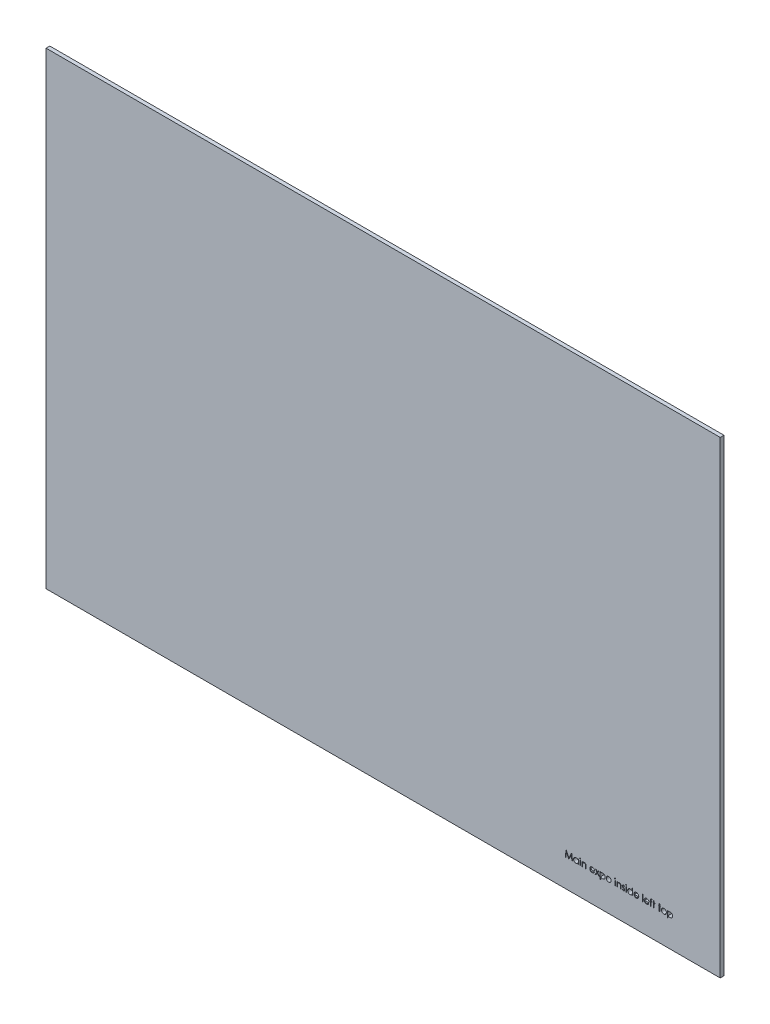
SolidWorks part; units mm, degrees
ref_plane "Front Plane" through (0, 0, 0) normal (0, 0, 1) x (1, 0, 0)
ref_plane "Top Plane" through (0, 0, 0) normal (0, 1, 0) x (1, 0, 0)
ref_plane "Right Plane" through (0, 0, 0) normal (1, 0, 0) x (0, 0, -1)
sketch "Sketch1" plane through (0, 0, 0) normal (0, 0, 1) x (1, 0, 0)
  line L1 (0, 0) -> (360, 0)
  line L2 (0, 0) -> (0, -250)
  line L3 (0, -250) -> (360, -250)
  line L4 (360, 0) -> (360, -250)
  dimension "D1" = 360
  dimension "D2" = 250
extrude "Boss-Extrude1" add sketch "Sketch1" along normal blind 2
sketch "Sketch2" plane through (0, 0, 2) normal (0, 0, 1) x (1, 0, 0)
  line L0 (276.9828, -235.434) -> (341.8174, -235.434) construction
  line L1 (277.2521, -235.434) -> (277.7141, -231.934)
  line L2 (277.7141, -231.934) -> (277.759, -231.934)
  line L3 (277.759, -231.934) -> (279.204, -234.8058)
  line L4 (279.204, -234.8058) -> (280.6455, -231.934)
  line L5 (280.6455, -231.934) -> (280.6911, -231.934)
  line L6 (280.6911, -231.934) -> (281.1559, -235.434)
  line L7 (281.1559, -235.434) -> (280.8404, -235.434)
  line L8 (280.8404, -235.434) -> (280.5053, -232.9156)
  line L9 (280.5053, -232.9156) -> (279.2419, -235.434)
  line L10 (279.2419, -235.434) -> (279.171, -235.434)
  line L11 (279.171, -235.434) -> (277.9027, -232.91)
  line L12 (277.9027, -232.91) -> (277.5683, -235.434)
  line L13 (277.5683, -235.434) -> (277.2521, -235.434)
  line L14 (284.3867, -232.8763) -> (284.3867, -235.434)
  line L15 (284.3867, -235.434) -> (284.0726, -235.434)
  line L16 (284.0726, -235.434) -> (284.0726, -234.9916)
  line L17 (284.0726, -233.3496) -> (284.0726, -232.8763)
  line L18 (284.0726, -232.8763) -> (284.3867, -232.8763)
  line L19 (285.0598, -232.8763) -> (285.3739, -232.8763)
  line L20 (285.3739, -232.8763) -> (285.3739, -235.434)
  line L21 (285.3739, -235.434) -> (285.0598, -235.434)
  line L22 (285.0598, -235.434) -> (285.0598, -232.8763)
  line L23 (286.1367, -232.8763) -> (286.4508, -232.8763)
  line L24 (286.4508, -232.8763) -> (286.4508, -233.3376)
  line L25 (288.3803, -234.1278) -> (288.3803, -235.434)
  line L26 (288.3803, -235.434) -> (288.0662, -235.434)
  line L27 (288.0662, -235.434) -> (288.0662, -234.2309)
  line L28 (286.4508, -234.5092) -> (286.4508, -235.434)
  line L29 (286.4508, -235.434) -> (286.1367, -235.434)
  line L30 (286.1367, -235.434) -> (286.1367, -232.8763)
  line L31 (292.5435, -234.6263) -> (292.8226, -234.7728)
  line L32 (292.9572, -234.2225) -> (290.6687, -234.2225)
  line L33 (290.7017, -233.9084) -> (292.6431, -233.9084)
  line L34 (293.361, -232.8763) -> (293.7347, -232.8763)
  line L35 (293.7347, -232.8763) -> (294.3931, -233.799)
  line L36 (294.3931, -233.799) -> (295.0515, -232.8763)
  line L37 (295.0515, -232.8763) -> (295.4251, -232.8763)
  line L38 (295.4251, -232.8763) -> (294.5803, -234.0605)
  line L39 (294.5803, -234.0605) -> (295.5598, -235.434)
  line L40 (295.5598, -235.434) -> (295.1861, -235.434)
  line L41 (295.1861, -235.434) -> (294.3931, -234.3227)
  line L42 (294.3931, -234.3227) -> (293.6001, -235.434)
  line L43 (293.6001, -235.434) -> (293.2264, -235.434)
  line L44 (293.2264, -235.434) -> (294.2066, -234.0605)
  line L45 (294.2066, -234.0605) -> (293.361, -232.8763)
  line L46 (295.9187, -232.8763) -> (296.2328, -232.8763)
  line L47 (296.2328, -232.8763) -> (296.2328, -233.3496)
  line L48 (296.2328, -234.9706) -> (296.2328, -236.3763)
  line L49 (296.2328, -236.3763) -> (295.9187, -236.3763)
  line L50 (295.9187, -236.3763) -> (295.9187, -232.8763)
  line L51 (303.7264, -232.8763) -> (304.0405, -232.8763)
  line L52 (304.0405, -232.8763) -> (304.0405, -235.434)
  line L53 (304.0405, -235.434) -> (303.7264, -235.434)
  line L54 (303.7264, -235.434) -> (303.7264, -232.8763)
  line L55 (304.8034, -232.8763) -> (305.1175, -232.8763)
  line L56 (305.1175, -232.8763) -> (305.1175, -233.3376)
  line L57 (307.0469, -234.1278) -> (307.0469, -235.434)
  line L58 (307.0469, -235.434) -> (306.7328, -235.434)
  line L59 (306.7328, -235.434) -> (306.7328, -234.2309)
  line L60 (305.1175, -234.5092) -> (305.1175, -235.434)
  line L61 (305.1175, -235.434) -> (304.8034, -235.434)
  line L62 (304.8034, -235.434) -> (304.8034, -232.8763)
  line L63 (308.9764, -233.1953) -> (308.7633, -233.4148)
  line L64 (307.5405, -235.1325) -> (307.7488, -234.8955)
  line L65 (309.6046, -232.8763) -> (309.9187, -232.8763)
  line L66 (309.9187, -232.8763) -> (309.9187, -235.434)
  line L67 (309.9187, -235.434) -> (309.6046, -235.434)
  line L68 (309.6046, -235.434) -> (309.6046, -232.8763)
  line L69 (313.2841, -231.8443) -> (313.2841, -235.434)
  line L70 (313.2841, -235.434) -> (312.97, -235.434)
  line L71 (312.97, -235.434) -> (312.97, -234.9916)
  line L72 (312.97, -233.3713) -> (312.97, -231.8443)
  line L73 (312.97, -231.8443) -> (313.2841, -231.8443)
  line L74 (316.1012, -234.6263) -> (316.3803, -234.7728)
  line L75 (316.5149, -234.2225) -> (314.2264, -234.2225)
  line L76 (314.2594, -233.9084) -> (316.2008, -233.9084)
  line L77 (318.4444, -231.8443) -> (318.7585, -231.8443)
  line L78 (318.7585, -231.8443) -> (318.7585, -235.434)
  line L79 (318.7585, -235.434) -> (318.4444, -235.434)
  line L80 (318.4444, -235.434) -> (318.4444, -231.8443)
  line L81 (321.5756, -234.6263) -> (321.8546, -234.7728)
  line L82 (321.9893, -234.2225) -> (319.7008, -234.2225)
  line L83 (319.7337, -233.9084) -> (321.6751, -233.9084)
  line L84 (323.6944, -231.8653) -> (323.6944, -232.192)
  line L85 (323.1132, -232.5215) -> (323.1132, -232.8763)
  line L86 (323.1132, -232.8763) -> (323.6495, -232.8763)
  line L87 (323.6495, -232.8763) -> (323.6495, -233.1904)
  line L88 (323.6495, -233.1904) -> (323.1124, -233.1904)
  line L89 (323.1124, -233.1904) -> (323.111, -235.434)
  line L90 (323.111, -235.434) -> (322.7969, -235.434)
  line L91 (322.7969, -235.434) -> (322.7969, -233.1904)
  line L92 (322.7969, -233.1904) -> (322.438, -233.1904)
  line L93 (322.438, -233.1904) -> (322.438, -232.8763)
  line L94 (322.438, -232.8763) -> (322.7969, -232.8763)
  line L95 (322.7969, -232.8763) -> (322.7969, -232.4676)
  line L96 (324.4572, -231.8443) -> (324.7713, -231.8443)
  line L97 (324.7713, -231.8443) -> (324.7713, -232.8763)
  line L98 (324.7713, -232.8763) -> (325.22, -232.8763)
  line L99 (325.22, -232.8763) -> (325.22, -233.1904)
  line L100 (325.22, -233.1904) -> (324.7713, -233.1904)
  line L101 (324.7713, -233.1904) -> (324.7713, -235.434)
  line L102 (324.7713, -235.434) -> (324.4572, -235.434)
  line L103 (324.4572, -235.434) -> (324.4572, -233.1904)
  line L104 (324.4572, -233.1904) -> (324.0085, -233.1904)
  line L105 (324.0085, -233.1904) -> (324.0085, -232.8763)
  line L106 (324.0085, -232.8763) -> (324.4572, -232.8763)
  line L107 (324.4572, -232.8763) -> (324.4572, -231.8443)
  line L108 (327.4187, -231.8443) -> (327.7328, -231.8443)
  line L109 (327.7328, -231.8443) -> (327.7328, -232.8763)
  line L110 (327.7328, -232.8763) -> (328.1816, -232.8763)
  line L111 (328.1816, -232.8763) -> (328.1816, -233.1904)
  line L112 (328.1816, -233.1904) -> (327.7328, -233.1904)
  line L113 (327.7328, -233.1904) -> (327.7328, -235.434)
  line L114 (327.7328, -235.434) -> (327.4187, -235.434)
  line L115 (327.4187, -235.434) -> (327.4187, -233.1904)
  line L116 (327.4187, -233.1904) -> (326.97, -233.1904)
  line L117 (326.97, -233.1904) -> (326.97, -232.8763)
  line L118 (326.97, -232.8763) -> (327.4187, -232.8763)
  line L119 (327.4187, -232.8763) -> (327.4187, -231.8443)
  line L120 (331.9059, -232.8763) -> (332.22, -232.8763)
  line L121 (332.22, -232.8763) -> (332.22, -233.3496)
  line L122 (332.22, -234.9706) -> (332.22, -236.3763)
  line L123 (332.22, -236.3763) -> (331.9059, -236.3763)
  line L124 (331.9059, -236.3763) -> (331.9059, -232.8763)
  spline S0 degree 3 poles (284.0726, -234.9916) (284.0053, -235.071) (283.8968, -235.1816) (283.7302, -235.2962) (283.6015, -235.3644) (283.4666, -235.4155) (283.2766, -235.4649) (283.1281, -235.4797) (283.0279, -235.4789) knots 0 0 0 0 0.262085 0.38627 0.507165 0.6273 0.748145 1 1 1 1
  spline S1 degree 3 poles (283.0279, -235.4789) (282.9389, -235.4787) (282.8066, -235.4672) (282.6366, -235.4263) (282.5153, -235.3844) (282.3996, -235.3288) (282.2885, -235.2623) (282.1827, -235.1831) (282.0836, -235.0925) (281.9924, -234.9941) (281.9123, -234.8891) (281.8456, -234.7781) (281.7897, -234.6624) (281.7468, -234.5411) (281.7061, -234.3703) (281.6946, -234.2376) (281.6944, -234.1481) knots 0 0 0 0 0.127433 0.189004 0.24993 0.310668 0.372329 0.434939 0.499576 0.564191 0.626735 0.688109 0.749294 0.810331 0.871901 1 1 1 1
  spline S2 degree 3 poles (281.6944, -234.1481) (281.6949, -234.0603) (281.7056, -233.9297) (281.7476, -233.762) (281.7911, -233.6426) (281.847, -233.5283) (281.9149, -233.4189) (281.9949, -233.3141) (282.0872, -233.2164) (282.1871, -233.1262) (282.294, -233.0478) (282.4053, -232.9801) (282.5225, -232.9264) (282.6441, -232.8831) (282.8153, -232.8424) (282.9483, -232.8322) (283.0377, -232.8314) knots 0 0 0 0 0.126079 0.186904 0.247574 0.308003 0.369132 0.432033 0.496791 0.561611 0.624914 0.686726 0.748079 0.809582 0.871631 1 1 1 1
  spline S3 degree 3 poles (283.0377, -232.8314) (283.1399, -232.8317) (283.2917, -232.8449) (283.4837, -232.8988) (283.6183, -232.9527) (283.7455, -233.0244) (283.9074, -233.1475) (284.0107, -233.2646) (284.0726, -233.3496) knots 0 0 0 0 0.254654 0.376015 0.495255 0.614798 0.738106 1 1 1 1
  spline S4 degree 3 poles (283.0419, -233.1455) (282.9514, -233.1459) (282.8161, -233.1609) (282.645, -233.2175) (282.5241, -233.2747) (282.4114, -233.3468) (282.3107, -233.4339) (282.2212, -233.5337) (282.1459, -233.6458) (282.0846, -233.766) (282.0267, -233.9331) (282.0073, -234.0642) (282.0085, -234.1516) knots 0 0 0 0 0.169593 0.252476 0.336244 0.419505 0.502036 0.584775 0.669846 0.754185 0.836658 1 1 1 1
  spline S5 degree 3 poles (282.0085, -234.1516) (282.0092, -234.2386) (282.0259, -234.3701) (282.0858, -234.5369) (282.1469, -234.6581) (282.2236, -234.7707) (282.3125, -234.8725) (282.4145, -234.96) (282.5274, -235.0332) (282.648, -235.0923) (282.8175, -235.1477) (282.9502, -235.1652) (283.0391, -235.1648) knots 0 0 0 0 0.162859 0.245484 0.330807 0.416493 0.499893 0.583048 0.667158 0.751312 0.833785 1 1 1 1
  spline S6 degree 3 poles (283.0391, -235.1648) (283.1294, -235.1644) (283.2651, -235.1488) (283.4379, -235.0927) (283.5617, -235.0349) (283.677, -234.9631) (283.7805, -234.8791) (283.868, -234.7814) (283.9422, -234.674) (284.0003, -234.5563) (284.0579, -234.3869) (284.0721, -234.2514) (284.0726, -234.1608) knots 0 0 0 0 0.168664 0.252552 0.33824 0.423103 0.505556 0.586176 0.667136 0.748499 0.830452 1 1 1 1
  spline S7 degree 3 poles (284.0726, -234.1608) (284.0724, -234.0912) (284.0635, -233.9882) (284.0323, -233.856) (284, -233.7626) (283.9575, -233.6739) (283.9063, -233.5895) (283.8454, -233.5096) (283.7758, -233.4355) (283.6996, -233.3678) (283.619, -233.3075) (283.533, -233.2579) (283.4431, -233.2168) (283.3491, -233.1842) (283.2155, -233.1545) (283.112, -233.1445) (283.0419, -233.1455) knots 0 0 0 0 0.129188 0.191219 0.251913 0.312507 0.373494 0.435152 0.498741 0.562095 0.624187 0.685476 0.746097 0.807612 0.869967 1 1 1 1
  spline S8 degree 3 poles (285.2154, -231.7994) (285.2534, -231.7995) (285.3108, -231.8082) (285.3785, -231.8429) (285.4231, -231.8774) (285.4613, -231.918) (285.4973, -231.9811) (285.5087, -232.0344) (285.5085, -232.07) knots 0 0 0 0 0.258284 0.384341 0.51198 0.638632 0.75923 1 1 1 1
  spline S9 degree 3 poles (285.5085, -232.07) (285.5086, -232.105) (285.4972, -232.1574) (285.4611, -232.2194) (285.4231, -232.2599) (285.3785, -232.2943) (285.3108, -232.3291) (285.2534, -232.3378) (285.2154, -232.3378) knots 0 0 0 0 0.237546 0.357497 0.484917 0.613329 0.74015 1 1 1 1
  spline S10 degree 3 poles (285.2154, -232.3378) (285.178, -232.3381) (285.1215, -232.3287) (285.0544, -232.2943) (285.0098, -232.2601) (284.9726, -232.2191) (284.9363, -232.1575) (284.9251, -232.1049) (284.9251, -232.07) knots 0 0 0 0 0.256661 0.384213 0.513365 0.640443 0.761085 1 1 1 1
  spline S11 degree 3 poles (284.9251, -232.07) (284.925, -232.0344) (284.9362, -231.981) (284.9724, -231.9182) (285.0098, -231.8772) (285.0544, -231.843) (285.1215, -231.8086) (285.178, -231.7991) (285.2154, -231.7994) knots 0 0 0 0 0.242149 0.363437 0.489745 0.618115 0.744894 1 1 1 1
  spline S12 degree 3 poles (286.4508, -233.3376) (286.5141, -233.2554) (286.615, -233.1405) (286.7724, -233.02) (286.8923, -232.9498) (287.018, -232.897) (287.1935, -232.8454) (287.3315, -232.8319) (287.4239, -232.8314) knots 0 0 0 0 0.273569 0.398988 0.51993 0.63811 0.756589 1 1 1 1
  spline S13 degree 3 poles (287.4239, -232.8314) (287.5163, -232.832) (287.6542, -232.847) (287.8248, -232.9098) (287.9414, -232.973) (288.0465, -233.0516) (288.1388, -233.1432) (288.2152, -233.2485) (288.2664, -233.3462) (288.3001, -233.4329) (288.3214, -233.5071) (288.3394, -233.5899) (288.355, -233.6808) (288.3656, -233.7806) (288.3772, -233.9303) (288.3811, -234.0471) (288.3803, -234.1278) knots 0 0 0 0 0.151178 0.223488 0.295543 0.366976 0.437131 0.507044 0.57856 0.616614 0.658756 0.704491 0.754803 0.809332 0.868274 1 1 1 1
  spline S14 degree 3 poles (288.0662, -234.2309) (288.0657, -234.1643) (288.0656, -234.0689) (288.0616, -233.9476) (288.0577, -233.8702) (288.0519, -233.802) (288.0445, -233.729) (288.0361, -233.679) (288.029, -233.6489) knots 0 0 0 0 0.34211 0.489826 0.623254 0.74008 0.841483 1 1 1 1
  spline S15 degree 3 poles (288.029, -233.6489) (288.0115, -233.5721) (287.9718, -233.4625) (287.8836, -233.3409) (287.8057, -233.2687) (287.7145, -233.2126) (287.57, -233.1584) (287.4509, -233.1451) (287.3693, -233.1455) knots 0 0 0 0 0.260833 0.378476 0.493178 0.609281 0.729981 1 1 1 1
  spline S16 degree 3 poles (287.3693, -233.1455) (287.3193, -233.1453) (287.2446, -233.151) (287.1479, -233.1719) (287.0775, -233.1927) (287.01, -233.2214) (286.9432, -233.2539) (286.8797, -233.2945) (286.8181, -233.3397) (286.7608, -233.3897) (286.7075, -233.4426) (286.6599, -233.4989) (286.6169, -233.5577) (286.5797, -233.6198) (286.5362, -233.7065) (286.5118, -233.7756) (286.4992, -233.8228) knots 0 0 0 0 0.126627 0.188984 0.25023 0.312351 0.374574 0.438148 0.50292 0.567974 0.630771 0.692935 0.754398 0.815218 0.876117 1 1 1 1
  spline S17 degree 3 poles (286.4992, -233.8228) (286.4898, -233.8602) (286.4794, -233.9217) (286.469, -234.0106) (286.4619, -234.0915) (286.4576, -234.1822) (286.4511, -234.3224) (286.4513, -234.4326) (286.4508, -234.5092) knots 0 0 0 0 0.167615 0.271052 0.38946 0.520843 0.666399 1 1 1 1
  spline S18 degree 3 poles (292.8226, -234.7728) (292.7811, -234.8505) (292.7116, -234.9595) (292.6047, -235.0893) (292.5196, -235.171) (292.4299, -235.2423) (292.3352, -235.3046) (292.2349, -235.3577) (292.129, -235.4025) (292.0167, -235.4369) (291.8544, -235.4702) (291.7275, -235.4789) (291.6412, -235.4789) knots 0 0 0 0 0.181661 0.265874 0.346355 0.4246 0.501903 0.579992 0.658443 0.738672 0.821894 1 1 1 1
  spline S19 degree 3 poles (291.6412, -235.4789) (291.5454, -235.4788) (291.4045, -235.4678) (291.2253, -235.4247) (291.1021, -235.3808) (290.9873, -235.3233) (290.8808, -235.2534) (290.782, -235.1712) (290.694, -235.0762) (290.6147, -234.9745) (290.5448, -234.8686) (290.4863, -234.7586) (290.4388, -234.6453) (290.4004, -234.5295) (290.3643, -234.369) (290.3556, -234.2452) (290.3546, -234.1622) knots 0 0 0 0 0.139629 0.204797 0.268135 0.329814 0.391301 0.453434 0.516552 0.579631 0.641119 0.701294 0.76081 0.819932 0.87892 1 1 1 1
  spline S20 degree 3 poles (290.3546, -234.1622) (290.3556, -234.0844) (290.3629, -233.9682) (290.3945, -233.8177) (290.4266, -233.7088) (290.4682, -233.6033) (290.5364, -233.4658) (290.6016, -233.3697) (290.6491, -233.3082) knots 0 0 0 0 0.253768 0.377428 0.500551 0.623296 0.746578 1 1 1 1
  spline S21 degree 3 poles (290.6491, -233.3082) (290.7097, -233.2325) (290.8084, -233.1266) (290.9631, -233.0158) (291.0847, -232.9478) (291.215, -232.8962) (291.4016, -232.8437) (291.5495, -232.8326) (291.6489, -232.8314) knots 0 0 0 0 0.253589 0.374643 0.49534 0.616325 0.739759 1 1 1 1
  spline S22 degree 3 poles (291.6489, -232.8314) (291.7517, -232.831) (291.9036, -232.8459) (292.0962, -232.8992) (292.2301, -232.9543) (292.3557, -233.0255) (292.514, -233.1445) (292.6175, -233.2542) (292.6789, -233.3348) knots 0 0 0 0 0.259033 0.38188 0.502258 0.622752 0.744743 1 1 1 1
  spline S23 degree 3 poles (292.6789, -233.3348) (292.7247, -233.3937) (292.7847, -233.4894) (292.8483, -233.6262) (292.8866, -233.735) (292.9176, -233.8489) (292.9483, -234.0112) (292.9556, -234.1372) (292.9572, -234.2225) knots 0 0 0 0 0.236255 0.356174 0.47725 0.60154 0.729618 1 1 1 1
  spline S24 degree 3 poles (290.6687, -234.2225) (290.6705, -234.2887) (290.6794, -234.3866) (290.7097, -234.5118) (290.7409, -234.5989) (290.7788, -234.6818) (290.8252, -234.76) (290.8805, -234.833) (290.9423, -234.9016) (291.011, -234.9626) (291.0832, -235.0173) (291.1601, -235.0631) (291.241, -235.1003) (291.3258, -235.1293) (291.4458, -235.1564) (291.5389, -235.1651) (291.6019, -235.1648) knots 0 0 0 0 0.134476 0.198391 0.260753 0.321829 0.383037 0.444653 0.507398 0.569825 0.630778 0.690929 0.750945 0.811049 0.872331 1 1 1 1
  spline S25 degree 3 poles (291.6019, -235.1648) (291.6641, -235.1651) (291.7574, -235.1577) (291.8793, -235.1322) (291.9685, -235.1064) (292.0541, -235.0748) (292.1333, -235.0367) (292.2062, -234.9945) (292.2743, -234.9463) (292.3404, -234.8873) (292.4339, -234.7825) (292.501, -234.6929) (292.5435, -234.6263) knots 0 0 0 0 0.163879 0.245659 0.327726 0.40861 0.485749 0.559169 0.630268 0.705306 0.792065 1 1 1 1
  spline S26 degree 3 poles (292.6431, -233.9084) (292.6232, -233.8276) (292.5836, -233.7137) (292.5111, -233.5768) (292.4496, -233.4912) (292.3797, -233.4152) (292.2991, -233.3488) (292.2086, -233.2894) (292.1089, -233.2392) (292.0032, -233.1966) (291.8554, -233.158) (291.7415, -233.1444) (291.665, -233.1455) knots 0 0 0 0 0.185231 0.267501 0.3444 0.419595 0.496891 0.576638 0.660268 0.745387 0.83004 1 1 1 1
  spline S27 degree 3 poles (291.665, -233.1455) (291.6031, -233.1454) (291.5111, -233.1521) (291.3927, -233.1778) (291.308, -233.2037) (291.2274, -233.2384) (291.1224, -233.2928) (291.0515, -233.347) (291.006, -233.3853) knots 0 0 0 0 0.259141 0.384162 0.505992 0.629098 0.750669 1 1 1 1
  spline S28 degree 3 poles (291.006, -233.3853) (290.9711, -233.4147) (290.9239, -233.4656) (290.8672, -233.5404) (290.8278, -233.6034) (290.7917, -233.672) (290.7455, -233.7726) (290.7181, -233.853) (290.7017, -233.9084) knots 0 0 0 0 0.22258 0.3385 0.458709 0.585535 0.717518 1 1 1 1
  spline S29 degree 3 poles (296.2328, -233.3496) (296.295, -233.2643) (296.3994, -233.1483) (296.5607, -233.0241) (296.6878, -232.9527) (296.8223, -232.899) (297.0135, -232.8448) (297.1646, -232.8318) (297.2663, -232.8314) knots 0 0 0 0 0.263045 0.386061 0.505771 0.625178 0.746148 1 1 1 1
  spline S30 degree 3 poles (297.2663, -232.8314) (297.3559, -232.8323) (297.4892, -232.8423) (297.6606, -232.8831) (297.7822, -232.9264) (297.8995, -232.9801) (298.0107, -233.0478) (298.1176, -233.1262) (298.2175, -233.2164) (298.3098, -233.3141) (298.3897, -233.4191) (298.4586, -233.5281) (298.5142, -233.6427) (298.5578, -233.762) (298.5998, -233.9297) (298.6105, -234.0603) (298.611, -234.1481) knots 0 0 0 0 0.128636 0.190653 0.252125 0.313446 0.375227 0.438498 0.503285 0.56801 0.630879 0.692154 0.752552 0.813191 0.873985 1 1 1 1
  spline S31 degree 3 poles (298.611, -234.1481) (298.6108, -234.2377) (298.5993, -234.3703) (298.5587, -234.5411) (298.5157, -234.6623) (298.46, -234.7783) (298.3923, -234.8889) (298.3124, -234.9941) (298.2211, -235.0925) (298.1221, -235.1831) (298.0162, -235.2623) (297.9051, -235.3288) (297.7894, -235.3844) (297.6682, -235.4263) (297.4979, -235.4672) (297.3654, -235.4785) (297.2761, -235.4789) knots 0 0 0 0 0.128034 0.189574 0.25058 0.311733 0.37325 0.435763 0.500346 0.564949 0.627528 0.689157 0.749865 0.81076 0.8723 1 1 1 1
  spline S32 degree 3 poles (297.2761, -235.4789) (297.1756, -235.48) (297.0271, -235.4629) (296.8368, -235.4103) (296.7026, -235.3537) (296.5745, -235.2814) (296.4094, -235.1619) (296.3004, -235.0507) (296.2328, -234.9706) knots 0 0 0 0 0.250548 0.37123 0.492116 0.613401 0.737997 1 1 1 1
  spline S33 degree 3 poles (297.2635, -233.1455) (297.1934, -233.1445) (297.09, -233.1546) (296.9563, -233.1842) (296.8622, -233.2171) (296.7719, -233.2575) (296.6862, -233.3079) (296.6052, -233.3676) (296.529, -233.4353) (296.4601, -233.5098) (296.3991, -233.5894) (296.3479, -233.6739) (296.3054, -233.7626) (296.2731, -233.856) (296.2419, -233.9882) (296.233, -234.0912) (296.2328, -234.1608) knots 0 0 0 0 0.130024 0.192374 0.253884 0.314896 0.375806 0.438242 0.501591 0.564881 0.626533 0.687516 0.748106 0.808796 0.870822 1 1 1 1
  spline S34 degree 3 poles (296.2328, -234.1608) (296.233, -234.2515) (296.2481, -234.3866) (296.3042, -234.5565) (296.3626, -234.6739) (296.4366, -234.7819) (296.5257, -234.8786) (296.6291, -234.9634) (296.7452, -235.0348) (296.8696, -235.0927) (297.0428, -235.1485) (297.1783, -235.1646) (297.2684, -235.1648) knots 0 0 0 0 0.169344 0.251061 0.332326 0.413189 0.494299 0.576654 0.661785 0.747765 0.831967 1 1 1 1
  spline S35 degree 3 poles (297.2684, -235.1648) (297.3569, -235.1653) (297.4891, -235.1474) (297.658, -235.0925) (297.7782, -235.033) (297.891, -234.96) (297.9929, -234.8724) (298.0819, -234.7709) (298.1577, -234.6579) (298.2188, -234.5368) (298.2801, -234.3703) (298.2959, -234.2385) (298.2969, -234.1516) knots 0 0 0 0 0.165574 0.248159 0.332033 0.416257 0.499525 0.583039 0.668596 0.754035 0.83692 1 1 1 1
  spline S36 degree 3 poles (298.2969, -234.1516) (298.2982, -234.0641) (298.2786, -233.9332) (298.2211, -233.7658) (298.1586, -233.6463) (298.0844, -233.5335) (297.9946, -233.4339) (297.894, -233.3468) (297.7813, -233.2747) (297.6604, -233.2175) (297.4894, -233.1609) (297.354, -233.1459) (297.2635, -233.1455) knots 0 0 0 0 0.163349 0.245826 0.330367 0.415198 0.497941 0.580476 0.66374 0.747513 0.830399 1 1 1 1
  spline S37 degree 3 poles (300.4746, -232.8314) (300.5687, -232.8305) (300.7079, -232.844) (300.8861, -232.8887) (301.0119, -232.9339) (301.1302, -232.9946) (301.2826, -233.0921) (301.3842, -233.1849) (301.4464, -233.2528) knots 0 0 0 0 0.258332 0.382134 0.503804 0.624693 0.746871 1 1 1 1
  spline S38 degree 3 poles (301.4464, -233.2528) (301.5034, -233.3151) (301.5798, -233.4151) (301.662, -233.5594) (301.7112, -233.6717) (301.7498, -233.788) (301.787, -233.951) (301.7965, -234.0772) (301.7969, -234.1622) knots 0 0 0 0 0.253834 0.376506 0.498534 0.621368 0.744565 1 1 1 1
  spline S39 degree 3 poles (301.7969, -234.1622) (301.7975, -234.2477) (301.7857, -234.3749) (301.7471, -234.5392) (301.7063, -234.6571) (301.654, -234.771) (301.5901, -234.8804) (301.5142, -234.9855) (301.4282, -235.0855) (301.3331, -235.1777) (301.23, -235.258) (301.1209, -235.3269) (301.0042, -235.3823) (300.8812, -235.426) (300.7051, -235.4678) (300.5676, -235.4785) (300.4746, -235.4789) knots 0 0 0 0 0.123337 0.183265 0.243172 0.302898 0.363774 0.425605 0.489659 0.553785 0.616222 0.677854 0.739517 0.802097 0.865866 1 1 1 1
  spline S40 degree 3 poles (300.4746, -235.4789) (300.3812, -235.4784) (300.2432, -235.468) (300.0667, -235.426) (299.9435, -235.3822) (299.8263, -235.3269) (299.7165, -235.2582) (299.6133, -235.1777) (299.5183, -235.0856) (299.4323, -234.9855) (299.3564, -234.8804) (299.2925, -234.771) (299.2401, -234.6571) (299.1993, -234.5392) (299.1607, -234.3749) (299.149, -234.2477) (299.1495, -234.1622) knots 0 0 0 0 0.134635 0.198324 0.260825 0.322714 0.384555 0.446913 0.510958 0.574931 0.636685 0.697483 0.757134 0.816966 0.876818 1 1 1 1
  spline S41 degree 3 poles (299.1495, -234.1622) (299.15, -234.0775) (299.1596, -233.9515) (299.1966, -233.789) (299.2353, -233.673) (299.2848, -233.5613) (299.366, -233.4165) (299.4437, -233.3174) (299.5001, -233.2549) knots 0 0 0 0 0.255238 0.378679 0.501088 0.622714 0.746241 1 1 1 1
  spline S42 degree 3 poles (299.5001, -233.2549) (299.5617, -233.1861) (299.6642, -233.0942) (299.8162, -232.9947) (299.9359, -232.9352) (300.0616, -232.8884) (300.2404, -232.8441) (300.3801, -232.8306) (300.4746, -232.8314) knots 0 0 0 0 0.252713 0.374819 0.496436 0.617911 0.741288 1 1 1 1
  spline S43 degree 3 poles (300.4732, -233.1455) (300.4062, -233.1457) (300.3067, -233.1548) (300.1787, -233.1859) (300.0873, -233.2184) (299.9997, -233.2605) (299.9157, -233.3122) (299.8353, -233.3729) (299.7599, -233.4423) (299.6907, -233.5182) (299.6303, -233.5991) (299.5788, -233.6836) (299.536, -233.7718) (299.5041, -233.8647) (299.4727, -233.9949) (299.4638, -234.0961) (299.4636, -234.1643) knots 0 0 0 0 0.126044 0.187165 0.247399 0.30838 0.36978 0.432584 0.497641 0.562401 0.625557 0.687332 0.748313 0.809791 0.871768 1 1 1 1
  spline S44 degree 3 poles (299.4636, -234.1643) (299.4638, -234.253) (299.4794, -234.3863) (299.5378, -234.5542) (299.5963, -234.6739) (299.6697, -234.7845) (299.7562, -234.8832) (299.8548, -234.9684) (299.9645, -235.0391) (300.0828, -235.0952) (300.2512, -235.149) (300.3839, -235.1658) (300.4732, -235.1648) knots 0 0 0 0 0.168179 0.251488 0.335841 0.419834 0.502345 0.583649 0.665931 0.748717 0.831047 1 1 1 1
  spline S45 degree 3 poles (300.4732, -235.1648) (300.5625, -235.1657) (300.6951, -235.1493) (300.8631, -235.095) (300.9813, -235.0391) (301.0909, -234.9681) (301.1902, -234.8837) (301.276, -234.7843) (301.3493, -234.6737) (301.4088, -234.5544) (301.4669, -234.3862) (301.4827, -234.253) (301.4828, -234.1643) knots 0 0 0 0 0.168983 0.250908 0.333708 0.416005 0.49766 0.579893 0.663902 0.748466 0.831791 1 1 1 1
  spline S46 degree 3 poles (301.4828, -234.1643) (301.4827, -234.0961) (301.4738, -233.9949) (301.4423, -233.8647) (301.4104, -233.7719) (301.3677, -233.6833) (301.3153, -233.5993) (301.2551, -233.5179) (301.1851, -233.4426) (301.1098, -233.3729) (301.0293, -233.3122) (300.9455, -233.2608) (300.8581, -233.2181) (300.7667, -233.1862) (300.6391, -233.1545) (300.5399, -233.1459) (300.4732, -233.1455) knots 0 0 0 0 0.128274 0.19027 0.251768 0.312769 0.374793 0.43797 0.503047 0.568125 0.63095 0.692369 0.752973 0.813641 0.874355 1 1 1 1
  spline S47 degree 3 poles (303.8821, -231.7994) (303.9201, -231.7995) (303.9775, -231.8082) (304.0452, -231.8429) (304.0898, -231.8774) (304.128, -231.918) (304.164, -231.9811) (304.1754, -232.0344) (304.1751, -232.07) knots 0 0 0 0 0.258284 0.384341 0.51198 0.638632 0.75923 1 1 1 1
  spline S48 degree 3 poles (304.1751, -232.07) (304.1752, -232.105) (304.1639, -232.1574) (304.1278, -232.2194) (304.0898, -232.2599) (304.0452, -232.2943) (303.9775, -232.3291) (303.9201, -232.3378) (303.8821, -232.3378) knots 0 0 0 0 0.237546 0.357497 0.484917 0.613329 0.74015 1 1 1 1
  spline S49 degree 3 poles (303.8821, -232.3378) (303.8447, -232.3381) (303.7882, -232.3287) (303.7211, -232.2943) (303.6764, -232.2601) (303.6393, -232.2191) (303.603, -232.1575) (303.5918, -232.1049) (303.5918, -232.07) knots 0 0 0 0 0.256661 0.384213 0.513365 0.640443 0.761085 1 1 1 1
  spline S50 degree 3 poles (303.5918, -232.07) (303.5917, -232.0344) (303.6029, -231.981) (303.639, -231.9182) (303.6765, -231.8772) (303.7211, -231.843) (303.7882, -231.8086) (303.8447, -231.7991) (303.8821, -231.7994) knots 0 0 0 0 0.242149 0.363437 0.489745 0.618115 0.744894 1 1 1 1
  spline S51 degree 3 poles (305.1175, -233.3376) (305.1808, -233.2554) (305.2817, -233.1405) (305.439, -233.02) (305.559, -232.9498) (305.6846, -232.897) (305.8601, -232.8454) (305.9982, -232.8319) (306.0906, -232.8314) knots 0 0 0 0 0.273569 0.398988 0.51993 0.63811 0.756589 1 1 1 1
  spline S52 degree 3 poles (306.0906, -232.8314) (306.183, -232.832) (306.3209, -232.847) (306.4914, -232.9098) (306.6081, -232.973) (306.7132, -233.0516) (306.8055, -233.1432) (306.8819, -233.2485) (306.9331, -233.3462) (306.9668, -233.4329) (306.988, -233.5071) (307.0061, -233.5899) (307.0217, -233.6808) (307.0323, -233.7806) (307.0439, -233.9303) (307.0477, -234.0471) (307.0469, -234.1278) knots 0 0 0 0 0.151178 0.223488 0.295543 0.366976 0.437131 0.507044 0.57856 0.616614 0.658756 0.704491 0.754803 0.809332 0.868274 1 1 1 1
  spline S53 degree 3 poles (306.7328, -234.2309) (306.7323, -234.1643) (306.7322, -234.0689) (306.7283, -233.9476) (306.7244, -233.8702) (306.7186, -233.802) (306.7112, -233.729) (306.7027, -233.679) (306.6957, -233.6489) knots 0 0 0 0 0.34211 0.489826 0.623254 0.74008 0.841483 1 1 1 1
  spline S54 degree 3 poles (306.6957, -233.6489) (306.6782, -233.5721) (306.6385, -233.4625) (306.5502, -233.3409) (306.4724, -233.2687) (306.3811, -233.2126) (306.2367, -233.1584) (306.1176, -233.1451) (306.0359, -233.1455) knots 0 0 0 0 0.260833 0.378476 0.493178 0.609281 0.729981 1 1 1 1
  spline S55 degree 3 poles (306.0359, -233.1455) (305.986, -233.1453) (305.9112, -233.151) (305.8146, -233.1719) (305.7442, -233.1927) (305.6767, -233.2214) (305.6099, -233.2539) (305.5464, -233.2945) (305.4848, -233.3397) (305.4275, -233.3897) (305.3741, -233.4426) (305.3266, -233.4989) (305.2835, -233.5577) (305.2464, -233.6198) (305.2028, -233.7065) (305.1784, -233.7756) (305.1658, -233.8228) knots 0 0 0 0 0.126627 0.188984 0.25023 0.312351 0.374574 0.438148 0.50292 0.567974 0.630771 0.692935 0.754398 0.815218 0.876117 1 1 1 1
  spline S56 degree 3 poles (305.1658, -233.8228) (305.1565, -233.8602) (305.146, -233.9217) (305.1357, -234.0106) (305.1286, -234.0915) (305.1243, -234.1822) (305.1178, -234.3224) (305.1179, -234.4326) (305.1175, -234.5092) knots 0 0 0 0 0.167615 0.271052 0.38946 0.520843 0.666399 1 1 1 1
  spline S57 degree 3 poles (308.7633, -233.4148) (308.7285, -233.3732) (308.675, -233.3153) (308.5972, -233.2513) (308.5421, -233.2123) (308.4867, -233.1829) (308.4146, -233.1547) (308.3584, -233.1456) (308.3216, -233.1455) knots 0 0 0 0 0.305036 0.441309 0.565963 0.683525 0.793334 1 1 1 1
  spline S58 degree 3 poles (308.3216, -233.1455) (308.2779, -233.1446) (308.2128, -233.1587) (308.1355, -233.2023) (308.0853, -233.2482) (308.0429, -233.301) (308.0012, -233.3798) (307.9894, -233.4458) (307.9893, -233.4898) knots 0 0 0 0 0.245901 0.369166 0.498511 0.628504 0.751028 1 1 1 1
  spline S59 degree 3 poles (307.9893, -233.4898) (307.9893, -233.5302) (308.005, -233.6143) (308.0495, -233.6873) (308.0762, -233.7219) knots 0 0 0 0 0.479403 1 1 1 1
  spline S60 degree 3 poles (308.0762, -233.7219) (308.0922, -233.7436) (308.1234, -233.7731) (308.169, -233.8133) (308.2122, -233.8453) (308.261, -233.8789) (308.3379, -233.9263) (308.3981, -233.9629) (308.4415, -233.9855) knots 0 0 0 0 0.17756 0.283982 0.402217 0.533568 0.676121 1 1 1 1
  spline S61 degree 3 poles (308.4415, -233.9855) (308.4942, -234.0146) (308.57, -234.0585) (308.6637, -234.1213) (308.7252, -234.166) (308.7791, -234.2111) (308.8408, -234.2674) (308.8799, -234.3132) (308.9021, -234.3445) knots 0 0 0 0 0.307115 0.446213 0.574876 0.694152 0.804581 1 1 1 1
  spline S62 degree 3 poles (308.9021, -234.3445) (308.9402, -234.402) (309.0042, -234.5286) (309.0203, -234.6696) (309.0213, -234.7399) knots 0 0 0 0 0.495235 1 1 1 1
  spline S63 degree 3 poles (309.0213, -234.7399) (309.0208, -234.7896) (309.0153, -234.8637) (308.9923, -234.9584) (308.9693, -235.0261) (308.9381, -235.0901) (308.9015, -235.1519) (308.8577, -235.2103) (308.8076, -235.2651) (308.7527, -235.3152) (308.6942, -235.3592) (308.632, -235.3958) (308.5664, -235.4261) (308.4975, -235.4501) (308.3995, -235.4728) (308.3232, -235.4785) (308.2718, -235.4789) knots 0 0 0 0 0.127199 0.188597 0.24864 0.309525 0.370037 0.431889 0.495704 0.559519 0.621372 0.682397 0.743568 0.805498 0.86864 1 1 1 1
  spline S64 degree 3 poles (308.2718, -235.4789) (308.2015, -235.4794) (308.0963, -235.4673) (307.9608, -235.4286) (307.8624, -235.3889) (307.7694, -235.3387) (307.6561, -235.2591) (307.5828, -235.1861) (307.5405, -235.1325) knots 0 0 0 0 0.251724 0.377219 0.504694 0.631458 0.755401 1 1 1 1
  spline S65 degree 3 poles (307.7488, -234.8955) (307.7864, -234.9374) (307.8447, -234.9961) (307.9306, -235.0596) (307.9934, -235.0983) (308.0576, -235.128) (308.1441, -235.1559) (308.2112, -235.165) (308.2557, -235.1648) knots 0 0 0 0 0.285904 0.417172 0.540501 0.659238 0.775006 1 1 1 1
  spline S66 degree 3 poles (308.2557, -235.1648) (308.3149, -235.1653) (308.4027, -235.15) (308.5084, -235.0982) (308.5765, -235.0442) (308.6343, -234.9812) (308.6904, -234.8869) (308.7075, -234.8064) (308.7072, -234.7532) knots 0 0 0 0 0.261896 0.387836 0.517686 0.644509 0.764718 1 1 1 1
  spline S67 degree 3 poles (308.7072, -234.7532) (308.707, -234.7092) (308.693, -234.6209) (308.6489, -234.5432) (308.621, -234.5092) knots 0 0 0 0 0.500453 1 1 1 1
  spline S68 degree 3 poles (308.621, -234.5092) (308.6041, -234.489) (308.5729, -234.4595) (308.525, -234.4215) (308.4799, -234.3891) (308.4279, -234.3555) (308.3452, -234.3069) (308.2796, -234.2701) (308.2332, -234.2456) knots 0 0 0 0 0.167462 0.27227 0.389551 0.520801 0.666263 1 1 1 1
  spline S69 degree 3 poles (308.2332, -234.2456) (308.1826, -234.2176) (308.1097, -234.1759) (308.0206, -234.1143) (307.9615, -234.0714) (307.9093, -234.0279) (307.8514, -233.9716) (307.8132, -233.9275) (307.7922, -233.8964) knots 0 0 0 0 0.30595 0.443775 0.572824 0.692154 0.802296 1 1 1 1
  spline S70 degree 3 poles (307.7922, -233.8964) (307.753, -233.84) (307.6946, -233.7121) (307.6739, -233.5731) (307.6751, -233.5024) knots 0 0 0 0 0.492591 1 1 1 1
  spline S71 degree 3 poles (307.6751, -233.5024) (307.6755, -233.4563) (307.6796, -233.3876) (307.7003, -233.3001) (307.7193, -233.2379) (307.7458, -233.1794) (307.7774, -233.1238) (307.8146, -233.071) (307.8575, -233.022) (307.9046, -232.9775) (307.9555, -232.9387) (308.009, -232.9056) (308.0654, -232.8778) (308.1252, -232.8569) (308.2104, -232.8371) (308.2767, -232.8309) (308.3216, -232.8314) knots 0 0 0 0 0.133044 0.196507 0.258613 0.319728 0.380873 0.442636 0.505079 0.567881 0.628814 0.68891 0.748765 0.809386 0.870884 1 1 1 1
  spline S72 degree 3 poles (308.3216, -232.8314) (308.3765, -232.8315) (308.4604, -232.8432) (308.5683, -232.8816) (308.6506, -232.9218) (308.7324, -232.9739) (308.8459, -233.0608) (308.9258, -233.138) (308.9764, -233.1953) knots 0 0 0 0 0.213412 0.326127 0.444452 0.569061 0.702712 1 1 1 1
  spline S73 degree 3 poles (309.7603, -231.7994) (309.7983, -231.7995) (309.8557, -231.8082) (309.9234, -231.8429) (309.968, -231.8774) (310.0062, -231.918) (310.0422, -231.9811) (310.0536, -232.0344) (310.0534, -232.07) knots 0 0 0 0 0.258284 0.384341 0.51198 0.638632 0.75923 1 1 1 1
  spline S74 degree 3 poles (310.0534, -232.07) (310.0534, -232.105) (310.0421, -232.1574) (310.006, -232.2194) (309.968, -232.2599) (309.9234, -232.2943) (309.8557, -232.3291) (309.7983, -232.3378) (309.7603, -232.3378) knots 0 0 0 0 0.237546 0.357497 0.484917 0.613329 0.74015 1 1 1 1
  spline S75 degree 3 poles (309.7603, -232.3378) (309.7229, -232.3381) (309.6664, -232.3287) (309.5993, -232.2943) (309.5546, -232.2601) (309.5175, -232.2191) (309.4812, -232.1575) (309.47, -232.1049) (309.47, -232.07) knots 0 0 0 0 0.256661 0.384213 0.513365 0.640443 0.761085 1 1 1 1
  spline S76 degree 3 poles (309.47, -232.07) (309.4699, -232.0344) (309.4811, -231.981) (309.5172, -231.9182) (309.5547, -231.8772) (309.5993, -231.843) (309.6664, -231.8086) (309.7229, -231.7991) (309.7603, -231.7994) knots 0 0 0 0 0.242149 0.363437 0.489745 0.618115 0.744894 1 1 1 1
  spline S77 degree 3 poles (312.97, -234.9916) (312.9028, -235.071) (312.7943, -235.1816) (312.6276, -235.2962) (312.499, -235.3644) (312.3641, -235.4155) (312.174, -235.4649) (312.0256, -235.4797) (311.9253, -235.4789) knots 0 0 0 0 0.262085 0.38627 0.507165 0.6273 0.748145 1 1 1 1
  spline S78 degree 3 poles (311.9253, -235.4789) (311.8363, -235.4787) (311.7041, -235.4672) (311.534, -235.4263) (311.4127, -235.3844) (311.297, -235.3288) (311.186, -235.2623) (311.0801, -235.1831) (310.981, -235.0925) (310.8898, -234.9941) (310.8097, -234.8891) (310.743, -234.7781) (310.6872, -234.6624) (310.6442, -234.5411) (310.6035, -234.3703) (310.592, -234.2376) (310.5918, -234.1481) knots 0 0 0 0 0.127433 0.189004 0.24993 0.310668 0.372329 0.434939 0.499576 0.564191 0.626735 0.688109 0.749294 0.810331 0.871901 1 1 1 1
  spline S79 degree 3 poles (310.5918, -234.1481) (310.5923, -234.0603) (310.6031, -233.9297) (310.6451, -233.762) (310.6886, -233.6426) (310.7444, -233.5283) (310.8123, -233.4189) (310.8924, -233.3141) (310.9846, -233.2164) (311.0846, -233.1262) (311.1915, -233.0478) (311.3027, -232.9801) (311.4199, -232.9264) (311.5415, -232.8831) (311.7127, -232.8424) (311.8458, -232.8322) (311.9352, -232.8314) knots 0 0 0 0 0.126079 0.186904 0.247574 0.308003 0.369132 0.432033 0.496791 0.561611 0.624914 0.686726 0.748079 0.809582 0.871631 1 1 1 1
  spline S80 degree 3 poles (311.9352, -232.8314) (312.0375, -232.8317) (312.1897, -232.8463) (312.3816, -232.905) (312.5161, -232.964) (312.6424, -233.0409) (312.8047, -233.1668) (312.9067, -233.2868) (312.97, -233.3713) knots 0 0 0 0 0.252985 0.37421 0.494102 0.614753 0.738511 1 1 1 1
  spline S81 degree 3 poles (311.9394, -233.1455) (311.8489, -233.1459) (311.7135, -233.1609) (311.5425, -233.2175) (311.4215, -233.2747) (311.3089, -233.3468) (311.2082, -233.4339) (311.1186, -233.5337) (311.0433, -233.6458) (310.982, -233.766) (310.9241, -233.9331) (310.9048, -234.0642) (310.9059, -234.1516) knots 0 0 0 0 0.169593 0.252476 0.336244 0.419505 0.502036 0.584775 0.669846 0.754185 0.836658 1 1 1 1
  spline S82 degree 3 poles (310.9059, -234.1516) (310.9067, -234.2386) (310.9233, -234.3701) (310.9832, -234.5369) (311.0444, -234.6581) (311.1211, -234.7707) (311.21, -234.8725) (311.3119, -234.96) (311.4248, -235.0332) (311.5454, -235.0923) (311.7149, -235.1477) (311.8477, -235.1652) (311.9366, -235.1648) knots 0 0 0 0 0.162859 0.245484 0.330807 0.416493 0.499893 0.583048 0.667158 0.751312 0.833785 1 1 1 1
  spline S83 degree 3 poles (311.9366, -235.1648) (312.0269, -235.1644) (312.1625, -235.1488) (312.3353, -235.0927) (312.4591, -235.0349) (312.5744, -234.9631) (312.6779, -234.8791) (312.7655, -234.7814) (312.8397, -234.674) (312.8978, -234.5563) (312.9553, -234.3869) (312.9695, -234.2514) (312.97, -234.1608) knots 0 0 0 0 0.168664 0.252552 0.33824 0.423103 0.505556 0.586176 0.667136 0.748499 0.830452 1 1 1 1
  spline S84 degree 3 poles (312.97, -234.1608) (312.9698, -234.0912) (312.961, -233.9882) (312.9298, -233.856) (312.8974, -233.7626) (312.8549, -233.6739) (312.8037, -233.5895) (312.7428, -233.5096) (312.6732, -233.4355) (312.597, -233.3678) (312.5165, -233.3075) (312.4305, -233.2579) (312.3406, -233.2168) (312.2465, -233.1842) (312.1129, -233.1545) (312.0095, -233.1445) (311.9394, -233.1455) knots 0 0 0 0 0.129188 0.191219 0.251913 0.312507 0.373494 0.435152 0.498741 0.562095 0.624187 0.685476 0.746097 0.807612 0.869967 1 1 1 1
  spline S85 degree 3 poles (316.3803, -234.7728) (316.3388, -234.8505) (316.2693, -234.9595) (316.1624, -235.0893) (316.0773, -235.171) (315.9876, -235.2423) (315.8929, -235.3046) (315.7926, -235.3577) (315.6867, -235.4025) (315.5744, -235.4369) (315.4121, -235.4702) (315.2852, -235.4789) (315.1989, -235.4789) knots 0 0 0 0 0.181661 0.265874 0.346355 0.4246 0.501903 0.579992 0.658443 0.738672 0.821894 1 1 1 1
  spline S86 degree 3 poles (315.1989, -235.4789) (315.1031, -235.4788) (314.9622, -235.4678) (314.783, -235.4247) (314.6598, -235.3808) (314.545, -235.3233) (314.4385, -235.2534) (314.3397, -235.1712) (314.2517, -235.0762) (314.1724, -234.9745) (314.1025, -234.8686) (314.044, -234.7586) (313.9965, -234.6453) (313.9581, -234.5295) (313.922, -234.369) (313.9132, -234.2452) (313.9123, -234.1622) knots 0 0 0 0 0.139629 0.204797 0.268135 0.329814 0.391301 0.453434 0.516552 0.579631 0.641119 0.701294 0.76081 0.819932 0.87892 1 1 1 1
  spline S87 degree 3 poles (313.9123, -234.1622) (313.9133, -234.0844) (313.9206, -233.9682) (313.9522, -233.8177) (313.9843, -233.7088) (314.0259, -233.6033) (314.0941, -233.4658) (314.1592, -233.3697) (314.2068, -233.3082) knots 0 0 0 0 0.253768 0.377428 0.500551 0.623296 0.746578 1 1 1 1
  spline S88 degree 3 poles (314.2068, -233.3082) (314.2674, -233.2325) (314.3661, -233.1266) (314.5208, -233.0158) (314.6424, -232.9478) (314.7727, -232.8962) (314.9593, -232.8437) (315.1071, -232.8326) (315.2066, -232.8314) knots 0 0 0 0 0.253589 0.374643 0.49534 0.616325 0.739759 1 1 1 1
  spline S89 degree 3 poles (315.2066, -232.8314) (315.3094, -232.831) (315.4613, -232.8459) (315.6539, -232.8992) (315.7878, -232.9543) (315.9134, -233.0255) (316.0717, -233.1445) (316.1752, -233.2542) (316.2365, -233.3348) knots 0 0 0 0 0.259033 0.38188 0.502258 0.622752 0.744743 1 1 1 1
  spline S90 degree 3 poles (316.2365, -233.3348) (316.2824, -233.3937) (316.3423, -233.4894) (316.406, -233.6262) (316.4443, -233.735) (316.4753, -233.8489) (316.5059, -234.0112) (316.5133, -234.1372) (316.5149, -234.2225) knots 0 0 0 0 0.236255 0.356174 0.47725 0.60154 0.729618 1 1 1 1
  spline S91 degree 3 poles (314.2264, -234.2225) (314.2282, -234.2887) (314.2371, -234.3866) (314.2674, -234.5118) (314.2986, -234.5989) (314.3365, -234.6818) (314.3829, -234.76) (314.4382, -234.833) (314.4999, -234.9016) (314.5687, -234.9626) (314.6409, -235.0173) (314.7178, -235.0631) (314.7987, -235.1003) (314.8835, -235.1293) (315.0035, -235.1564) (315.0966, -235.1651) (315.1596, -235.1648) knots 0 0 0 0 0.134476 0.198391 0.260753 0.321829 0.383037 0.444653 0.507398 0.569825 0.630778 0.690929 0.750945 0.811049 0.872331 1 1 1 1
  spline S92 degree 3 poles (315.1596, -235.1648) (315.2218, -235.1651) (315.3151, -235.1577) (315.437, -235.1322) (315.5262, -235.1064) (315.6118, -235.0748) (315.691, -235.0367) (315.7639, -234.9945) (315.832, -234.9463) (315.8981, -234.8873) (315.9916, -234.7825) (316.0587, -234.6929) (316.1012, -234.6263) knots 0 0 0 0 0.163879 0.245659 0.327726 0.40861 0.485749 0.559169 0.630268 0.705306 0.792065 1 1 1 1
  spline S93 degree 3 poles (316.2008, -233.9084) (316.1809, -233.8276) (316.1413, -233.7137) (316.0688, -233.5768) (316.0072, -233.4912) (315.9374, -233.4152) (315.8568, -233.3488) (315.7663, -233.2894) (315.6666, -233.2392) (315.5609, -233.1966) (315.4131, -233.158) (315.2992, -233.1444) (315.2227, -233.1455) knots 0 0 0 0 0.185231 0.267501 0.3444 0.419595 0.496891 0.576638 0.660268 0.745387 0.83004 1 1 1 1
  spline S94 degree 3 poles (315.2227, -233.1455) (315.1608, -233.1454) (315.0688, -233.1521) (314.9504, -233.1778) (314.8657, -233.2037) (314.7851, -233.2384) (314.6801, -233.2928) (314.6092, -233.347) (314.5637, -233.3853) knots 0 0 0 0 0.259141 0.384162 0.505992 0.629098 0.750669 1 1 1 1
  spline S95 degree 3 poles (314.5637, -233.3853) (314.5288, -233.4147) (314.4816, -233.4656) (314.4249, -233.5404) (314.3855, -233.6034) (314.3494, -233.672) (314.3032, -233.7726) (314.2758, -233.853) (314.2594, -233.9084) knots 0 0 0 0 0.22258 0.3385 0.458709 0.585535 0.717518 1 1 1 1
  spline S96 degree 3 poles (321.8546, -234.7728) (321.8131, -234.8505) (321.7437, -234.9595) (321.6367, -235.0893) (321.5516, -235.171) (321.462, -235.2423) (321.3672, -235.3046) (321.2669, -235.3577) (321.1611, -235.4025) (321.0488, -235.4369) (320.8864, -235.4702) (320.7595, -235.4789) (320.6732, -235.4789) knots 0 0 0 0 0.181661 0.265874 0.346355 0.4246 0.501903 0.579992 0.658443 0.738672 0.821894 1 1 1 1
  spline S97 degree 3 poles (320.6732, -235.4789) (320.5775, -235.4788) (320.4366, -235.4678) (320.2573, -235.4247) (320.1341, -235.3808) (320.0194, -235.3233) (319.9129, -235.2534) (319.814, -235.1712) (319.726, -235.0762) (319.6468, -234.9745) (319.5769, -234.8686) (319.5184, -234.7586) (319.4708, -234.6453) (319.4325, -234.5295) (319.3964, -234.369) (319.3876, -234.2452) (319.3867, -234.1622) knots 0 0 0 0 0.139629 0.204797 0.268135 0.329814 0.391301 0.453434 0.516552 0.579631 0.641119 0.701294 0.76081 0.819932 0.87892 1 1 1 1
  spline S98 degree 3 poles (319.3867, -234.1622) (319.3876, -234.0844) (319.3949, -233.9682) (319.4265, -233.8177) (319.4587, -233.7088) (319.5003, -233.6033) (319.5684, -233.4658) (319.6336, -233.3697) (319.6812, -233.3082) knots 0 0 0 0 0.253768 0.377428 0.500551 0.623296 0.746578 1 1 1 1
  spline S99 degree 3 poles (319.6812, -233.3082) (319.7417, -233.2325) (319.8405, -233.1266) (319.9952, -233.0158) (320.1167, -232.9478) (320.2471, -232.8962) (320.4336, -232.8437) (320.5815, -232.8326) (320.681, -232.8314) knots 0 0 0 0 0.253589 0.374643 0.49534 0.616325 0.739759 1 1 1 1
  spline S100 degree 3 poles (320.681, -232.8314) (320.7838, -232.831) (320.9357, -232.8459) (321.1283, -232.8992) (321.2621, -232.9543) (321.3878, -233.0255) (321.5461, -233.1445) (321.6495, -233.2542) (321.7109, -233.3348) knots 0 0 0 0 0.259033 0.38188 0.502258 0.622752 0.744743 1 1 1 1
  spline S101 degree 3 poles (321.7109, -233.3348) (321.7568, -233.3937) (321.8167, -233.4894) (321.8803, -233.6262) (321.9187, -233.735) (321.9497, -233.8489) (321.9803, -234.0112) (321.9877, -234.1372) (321.9893, -234.2225) knots 0 0 0 0 0.236255 0.356174 0.47725 0.60154 0.729618 1 1 1 1
  spline S102 degree 3 poles (319.7008, -234.2225) (319.7026, -234.2887) (319.7115, -234.3866) (319.7417, -234.5118) (319.773, -234.5989) (319.8109, -234.6818) (319.8572, -234.76) (319.9126, -234.833) (319.9743, -234.9016) (320.043, -234.9626) (320.1153, -235.0173) (320.1922, -235.0631) (320.2731, -235.1003) (320.3579, -235.1293) (320.4778, -235.1564) (320.571, -235.1651) (320.634, -235.1648) knots 0 0 0 0 0.134476 0.198391 0.260753 0.321829 0.383037 0.444653 0.507398 0.569825 0.630778 0.690929 0.750945 0.811049 0.872331 1 1 1 1
  spline S103 degree 3 poles (320.634, -235.1648) (320.6962, -235.1651) (320.7895, -235.1577) (320.9113, -235.1322) (321.0006, -235.1064) (321.0862, -235.0748) (321.1654, -235.0367) (321.2383, -234.9945) (321.3064, -234.9463) (321.3725, -234.8873) (321.4659, -234.7825) (321.5331, -234.6929) (321.5756, -234.6263) knots 0 0 0 0 0.163879 0.245659 0.327726 0.40861 0.485749 0.559169 0.630268 0.705306 0.792065 1 1 1 1
  spline S104 degree 3 poles (321.6751, -233.9084) (321.6553, -233.8276) (321.6157, -233.7137) (321.5432, -233.5768) (321.4816, -233.4912) (321.4118, -233.4152) (321.3311, -233.3488) (321.2407, -233.2894) (321.1409, -233.2392) (321.0353, -233.1966) (320.8875, -233.158) (320.7735, -233.1444) (320.6971, -233.1455) knots 0 0 0 0 0.185231 0.267501 0.3444 0.419595 0.496891 0.576638 0.660268 0.745387 0.83004 1 1 1 1
  spline S105 degree 3 poles (320.6971, -233.1455) (320.6352, -233.1454) (320.5431, -233.1521) (320.4248, -233.1778) (320.3401, -233.2037) (320.2595, -233.2384) (320.1544, -233.2928) (320.0835, -233.347) (320.038, -233.3853) knots 0 0 0 0 0.259141 0.384162 0.505992 0.629098 0.750669 1 1 1 1
  spline S106 degree 3 poles (320.038, -233.3853) (320.0031, -233.4147) (319.9559, -233.4656) (319.8992, -233.5404) (319.8599, -233.6034) (319.8238, -233.672) (319.7776, -233.7726) (319.7502, -233.853) (319.7337, -233.9084) knots 0 0 0 0 0.22258 0.3385 0.458709 0.585535 0.717518 1 1 1 1
  spline S107 degree 3 poles (323.6944, -232.192) (323.6383, -232.1686) (323.5346, -232.1308) (323.4253, -232.1137) (323.3761, -232.1135) knots 0 0 0 0 0.553028 1 1 1 1
  spline S108 degree 3 poles (323.3761, -232.1135) (323.3459, -232.1146) (323.3014, -232.1168) (323.2472, -232.1349) (323.2123, -232.152) (323.1833, -232.1733) (323.1585, -232.1948) (323.1406, -232.219) (323.1308, -232.2415) (323.1249, -232.2623) (323.1231, -232.2837) (323.1187, -232.3099) (323.1175, -232.3421) (323.1147, -232.3792) (323.1149, -232.4398) (323.1117, -232.4876) (323.1132, -232.5215) knots 0 0 0 0 0.158724 0.229424 0.297719 0.360776 0.416988 0.468546 0.516675 0.544534 0.581509 0.628334 0.683433 0.749506 0.822818 1 1 1 1
  spline S109 degree 3 poles (322.7969, -232.4676) (322.7961, -232.424) (322.7992, -232.3614) (322.8033, -232.2809) (322.8091, -232.2284) (322.8157, -232.1805) (322.8253, -232.1381) (322.8343, -232.1) (322.8506, -232.0569) (322.875, -232.0081) (322.9146, -231.9565) (322.962, -231.9102) (323.0186, -231.8711) (323.0823, -231.8387) (323.1795, -231.8068) (323.2583, -231.8003) (323.3116, -231.7994) knots 0 0 0 0 0.133856 0.192948 0.247916 0.296642 0.341504 0.38163 0.416905 0.483173 0.548917 0.616062 0.686302 0.759645 0.83539 1 1 1 1
  spline S110 degree 3 poles (323.3116, -231.7994) (323.3705, -231.8001) (323.5003, -231.8121) (323.6262, -231.846) (323.6944, -231.8653) knots 0 0 0 0 0.453863 1 1 1 1
  spline S111 degree 3 poles (329.9554, -232.8314) (330.0495, -232.8305) (330.1887, -232.844) (330.3668, -232.8887) (330.4926, -232.9339) (330.611, -232.9946) (330.7634, -233.0921) (330.865, -233.1849) (330.9272, -233.2528) knots 0 0 0 0 0.258332 0.382134 0.503804 0.624693 0.746871 1 1 1 1
  spline S112 degree 3 poles (330.9272, -233.2528) (330.9842, -233.3151) (331.0606, -233.4151) (331.1428, -233.5594) (331.1919, -233.6717) (331.2306, -233.788) (331.2678, -233.951) (331.2772, -234.0772) (331.2777, -234.1622) knots 0 0 0 0 0.253834 0.376506 0.498534 0.621368 0.744565 1 1 1 1
  spline S113 degree 3 poles (331.2777, -234.1622) (331.2782, -234.2477) (331.2665, -234.3749) (331.2279, -234.5392) (331.1871, -234.6571) (331.1347, -234.771) (331.0708, -234.8804) (330.995, -234.9855) (330.909, -235.0855) (330.8139, -235.1777) (330.7108, -235.258) (330.6016, -235.3269) (330.485, -235.3823) (330.3619, -235.426) (330.1859, -235.4678) (330.0483, -235.4785) (329.9554, -235.4789) knots 0 0 0 0 0.123337 0.183265 0.243172 0.302898 0.363774 0.425605 0.489659 0.553785 0.616222 0.677854 0.739517 0.802097 0.865866 1 1 1 1
  spline S114 degree 3 poles (329.9554, -235.4789) (329.862, -235.4784) (329.724, -235.468) (329.5475, -235.426) (329.4242, -235.3822) (329.3071, -235.3269) (329.1973, -235.2582) (329.0941, -235.1777) (328.999, -235.0856) (328.913, -234.9855) (328.8372, -234.8804) (328.7733, -234.771) (328.7209, -234.6571) (328.6801, -234.5392) (328.6415, -234.3749) (328.6298, -234.2477) (328.6303, -234.1622) knots 0 0 0 0 0.134635 0.198324 0.260825 0.322714 0.384555 0.446913 0.510958 0.574931 0.636685 0.697483 0.757134 0.816966 0.876818 1 1 1 1
  spline S115 degree 3 poles (328.6303, -234.1622) (328.6308, -234.0775) (328.6403, -233.9515) (328.6773, -233.789) (328.716, -233.673) (328.7656, -233.5613) (328.8467, -233.4165) (328.9244, -233.3174) (328.9808, -233.2549) knots 0 0 0 0 0.255238 0.378679 0.501088 0.622714 0.746241 1 1 1 1
  spline S116 degree 3 poles (328.9808, -233.2549) (329.0425, -233.1861) (329.145, -233.0942) (329.297, -232.9947) (329.4167, -232.9352) (329.5424, -232.8884) (329.7212, -232.8441) (329.8608, -232.8306) (329.9554, -232.8314) knots 0 0 0 0 0.252713 0.374819 0.496436 0.617911 0.741288 1 1 1 1
  spline S117 degree 3 poles (329.954, -233.1455) (329.887, -233.1457) (329.7875, -233.1548) (329.6595, -233.1859) (329.5681, -233.2184) (329.4804, -233.2605) (329.3965, -233.3122) (329.3161, -233.3729) (329.2407, -233.4423) (329.1715, -233.5182) (329.111, -233.5991) (329.0596, -233.6836) (329.0168, -233.7718) (328.9849, -233.8647) (328.9535, -233.9949) (328.9446, -234.0961) (328.9444, -234.1643) knots 0 0 0 0 0.126044 0.187165 0.247399 0.30838 0.36978 0.432584 0.497641 0.562401 0.625557 0.687332 0.748313 0.809791 0.871768 1 1 1 1
  spline S118 degree 3 poles (328.9444, -234.1643) (328.9446, -234.253) (328.9602, -234.3863) (329.0185, -234.5542) (329.0771, -234.6739) (329.1505, -234.7845) (329.237, -234.8832) (329.3356, -234.9684) (329.4452, -235.0391) (329.5636, -235.0952) (329.732, -235.149) (329.8647, -235.1658) (329.954, -235.1648) knots 0 0 0 0 0.168179 0.251488 0.335841 0.419834 0.502345 0.583649 0.665931 0.748717 0.831047 1 1 1 1
  spline S119 degree 3 poles (329.954, -235.1648) (330.0433, -235.1657) (330.1759, -235.1493) (330.3439, -235.095) (330.4621, -235.0391) (330.5717, -234.9681) (330.671, -234.8837) (330.7568, -234.7843) (330.8301, -234.6737) (330.8896, -234.5544) (330.9477, -234.3862) (330.9635, -234.253) (330.9636, -234.1643) knots 0 0 0 0 0.168983 0.250908 0.333708 0.416005 0.49766 0.579893 0.663902 0.748466 0.831791 1 1 1 1
  spline S120 degree 3 poles (330.9636, -234.1643) (330.9634, -234.0961) (330.9545, -233.9949) (330.9231, -233.8647) (330.8912, -233.7719) (330.8485, -233.6833) (330.7961, -233.5993) (330.7359, -233.5179) (330.6658, -233.4426) (330.5905, -233.3729) (330.5101, -233.3122) (330.4263, -233.2608) (330.3389, -233.2181) (330.2475, -233.1862) (330.1199, -233.1545) (330.0207, -233.1459) (329.954, -233.1455) knots 0 0 0 0 0.128274 0.19027 0.251768 0.312769 0.374793 0.43797 0.503047 0.568125 0.63095 0.692369 0.752973 0.813641 0.874355 1 1 1 1
  spline S121 degree 3 poles (332.22, -233.3496) (332.2822, -233.2643) (332.3866, -233.1483) (332.5479, -233.0241) (332.675, -232.9527) (332.8094, -232.899) (333.0007, -232.8448) (333.1518, -232.8318) (333.2535, -232.8314) knots 0 0 0 0 0.263045 0.386061 0.505771 0.625178 0.746148 1 1 1 1
  spline S122 degree 3 poles (333.2535, -232.8314) (333.3431, -232.8323) (333.4764, -232.8423) (333.6478, -232.8831) (333.7694, -232.9264) (333.8867, -232.9801) (333.9979, -233.0478) (334.1048, -233.1262) (334.2047, -233.2164) (334.297, -233.3141) (334.3769, -233.4191) (334.4457, -233.5281) (334.5014, -233.6427) (334.545, -233.762) (334.587, -233.9297) (334.5977, -234.0603) (334.5982, -234.1481) knots 0 0 0 0 0.128636 0.190653 0.252125 0.313446 0.375227 0.438498 0.503285 0.56801 0.630879 0.692154 0.752552 0.813191 0.873985 1 1 1 1
  spline S123 degree 3 poles (334.5982, -234.1481) (334.598, -234.2377) (334.5865, -234.3703) (334.5458, -234.5411) (334.5028, -234.6623) (334.4472, -234.7783) (334.3795, -234.8889) (334.2996, -234.9941) (334.2083, -235.0925) (334.1092, -235.1831) (334.0034, -235.2623) (333.8923, -235.3288) (333.7766, -235.3844) (333.6554, -235.4263) (333.4851, -235.4672) (333.3525, -235.4785) (333.2633, -235.4789) knots 0 0 0 0 0.128034 0.189574 0.25058 0.311733 0.37325 0.435763 0.500346 0.564949 0.627528 0.689157 0.749865 0.81076 0.8723 1 1 1 1
  spline S124 degree 3 poles (333.2633, -235.4789) (333.1628, -235.48) (333.0143, -235.4629) (332.824, -235.4103) (332.6898, -235.3537) (332.5617, -235.2814) (332.3966, -235.1619) (332.2876, -235.0507) (332.22, -234.9706) knots 0 0 0 0 0.250548 0.37123 0.492116 0.613401 0.737997 1 1 1 1
  spline S125 degree 3 poles (333.2507, -233.1455) (333.1806, -233.1445) (333.0771, -233.1546) (332.9435, -233.1842) (332.8494, -233.2171) (332.7591, -233.2575) (332.6734, -233.3079) (332.5924, -233.3676) (332.5161, -233.4353) (332.4473, -233.5098) (332.3863, -233.5894) (332.3351, -233.6739) (332.2926, -233.7626) (332.2603, -233.856) (332.2291, -233.9882) (332.2202, -234.0912) (332.22, -234.1608) knots 0 0 0 0 0.130024 0.192374 0.253884 0.314896 0.375806 0.438242 0.501591 0.564881 0.626533 0.687516 0.748106 0.808796 0.870822 1 1 1 1
  spline S126 degree 3 poles (332.22, -234.1608) (332.2202, -234.2515) (332.2353, -234.3866) (332.2913, -234.5565) (332.3498, -234.6739) (332.4238, -234.7819) (332.5129, -234.8786) (332.6163, -234.9634) (332.7324, -235.0348) (332.8568, -235.0927) (333.03, -235.1485) (333.1654, -235.1646) (333.2556, -235.1648) knots 0 0 0 0 0.169344 0.251061 0.332326 0.413189 0.494299 0.576654 0.661785 0.747765 0.831967 1 1 1 1
  spline S127 degree 3 poles (333.2556, -235.1648) (333.3441, -235.1653) (333.4762, -235.1474) (333.6452, -235.0925) (333.7653, -235.033) (333.8782, -234.96) (333.98, -234.8724) (334.069, -234.7709) (334.1449, -234.6579) (334.206, -234.5368) (334.2673, -234.3703) (334.2831, -234.2385) (334.2841, -234.1516) knots 0 0 0 0 0.165574 0.248159 0.332033 0.416257 0.499525 0.583039 0.668596 0.754035 0.83692 1 1 1 1
  spline S128 degree 3 poles (334.2841, -234.1516) (334.2854, -234.0641) (334.2658, -233.9332) (334.2083, -233.7658) (334.1458, -233.6463) (334.0716, -233.5335) (333.9818, -233.4339) (333.8812, -233.3468) (333.7685, -233.2747) (333.6476, -233.2175) (333.4765, -233.1609) (333.3412, -233.1459) (333.2507, -233.1455) knots 0 0 0 0 0.163349 0.245826 0.330367 0.415198 0.497941 0.580476 0.66374 0.747513 0.830399 1 1 1 1
extrude "Cut-Extrude1" cut sketch "Sketch2" against normal through all
